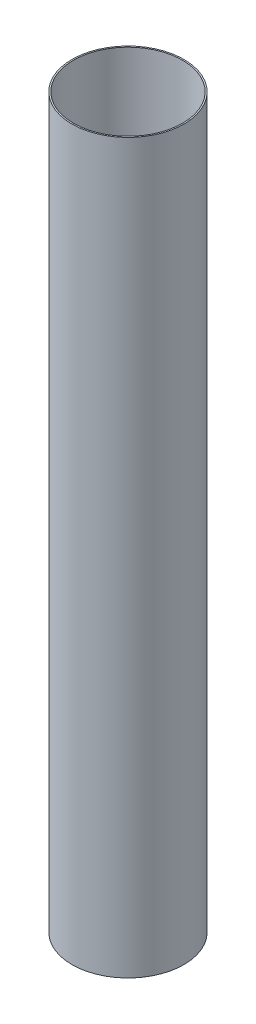
SolidWorks part; units mm, degrees
material "Corrugated Paper"
ref_plane "Front Plane" through (0, 0, 0) normal (0, 0, 1) x (1, 0, 0)
ref_plane "Top Plane" through (0, 0, 0) normal (0, 1, 0) x (1, 0, 0)
ref_plane "Right Plane" through (0, 0, 0) normal (1, 0, 0) x (0, 0, -1)
sketch "Sketch2" plane through (0, 0, 0) normal (0, 1, 0) x (1, 0, 0)
  circle A0 centre (0, 0) radius 40
  circle A1 centre (0, 0) radius 39
  dimension "D1" = 80
  dimension "D2" = 78
extrude "body" add sketch "Sketch2" along normal blind 520
equation "\"paper_size\" = 600mm"
equation "\"cb_roll_d_outer\" = 80mm"
equation "\"cb_roll_d_inner\" = 78mm"
